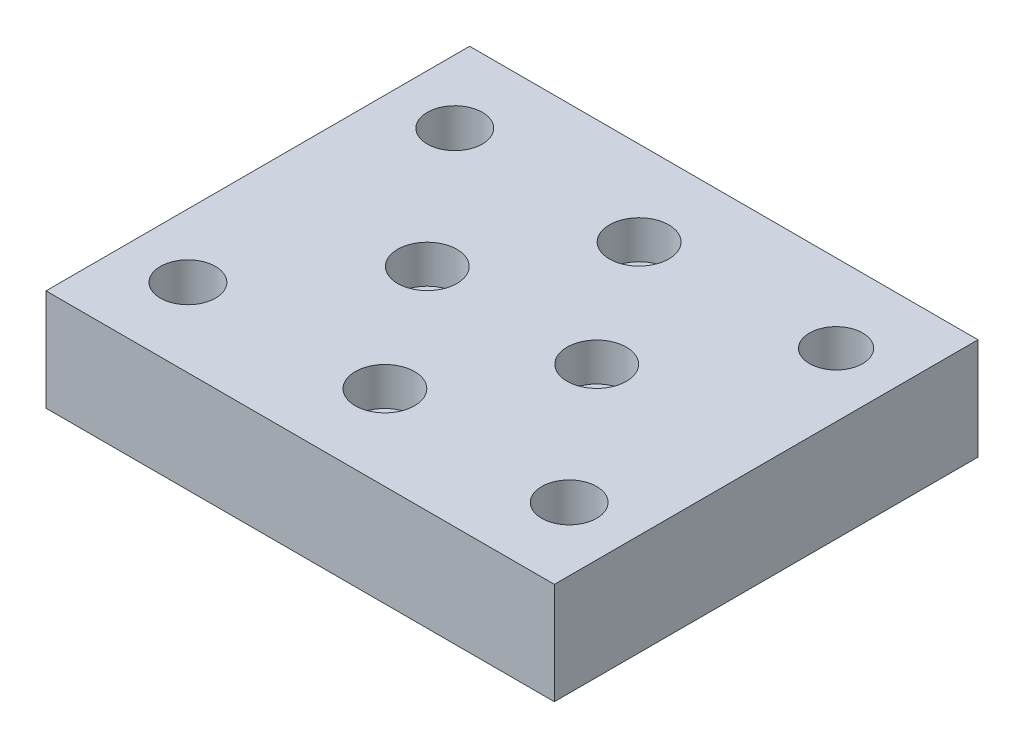
SolidWorks part; units mm, degrees
ref_plane "Alzado" through (0, 0, 0) normal (0, 0, 1) x (1, 0, 0)
ref_plane "Planta" through (0, 0, 0) normal (0, 1, 0) x (1, 0, 0)
ref_plane "Vista lateral" through (0, 0, 0) normal (1, 0, 0) x (0, 0, -1)
sketch "Croquis1" plane through (0, 0, 0) normal (0, 1, 0) x (1, 0, 0)
  line L1 (60, 50) -> (-60, 50)
  line L2 (60, 50) -> (60, -50)
  line L3 (60, -50) -> (-60, -50)
  line L4 (-60, 50) -> (-60, -50)
  line L5 (60, 50) -> (-60, -50) construction
  line L6 (60, -50) -> (-60, 50) construction
  point P0 (0, 0)
  dimension "D1" = 100
  dimension "D2" = 120
extrude "Saliente-Extruir1" add sketch "Croquis1" along normal blind 24
sketch "Croquis2" plane through (0, 24, 0) normal (0, 1, 0) x (1, 0, 0)
  circle A0 centre (0, 30) radius 7
  circle A1 centre (0, -30) radius 7
  circle A2 centre (-20, 0) radius 7
  circle A3 centre (20, 0) radius 7
  dimension "D5" = 14
  dimension "D1" = 30
  dimension "D2" = 30
  dimension "D3" = 20
  dimension "D4" = 20
extrude "Cortar-Extruir1" cut sketch "Croquis2" against normal blind 9
sketch "Croquis3" plane through (0, 15, 0) normal (0, 1, 0) x (1, 0, 0)
  circle A0 centre (-20, 0) radius 4.5
  circle A1 centre (0, 30) radius 4.5
  circle A2 centre (20, 0) radius 4.5
  circle A3 centre (0, -30) radius 4.5
  dimension "D1" = 9
extrude "Cortar-Extruir2" cut sketch "Croquis3" against normal up to next
sketch "Croquis4" plane through (0, 0, 0) normal (0, -1, 0) x (1, 0, 0)
  circle A0 centre (-45, 31.5) radius 9.5
  circle A1 centre (45, 31.5) radius 9.5
  circle A2 centre (45, -31.5) radius 9.5
  circle A3 centre (-45, -31.5) radius 9.5
  dimension "D3" = 45
  dimension "D5" = 19
  dimension "D1" = 31.5
  dimension "D2" = 31.5
  dimension "D4" = 45
extrude "Cortar-Extruir3" cut sketch "Croquis4" against normal blind 13
sketch "Croquis5" plane through (0, 13, 0) normal (0, -1, 0) x (1, 0, 0)
  circle A0 centre (-45, 31.5) radius 6.5
  circle A1 centre (45, 31.5) radius 6.5
  circle A2 centre (-45, -31.5) radius 6.5
  circle A3 centre (45, -31.5) radius 6.2769
  dimension "D1" = 13
extrude "Cortar-Extruir4" cut sketch "Croquis5" against normal through all
